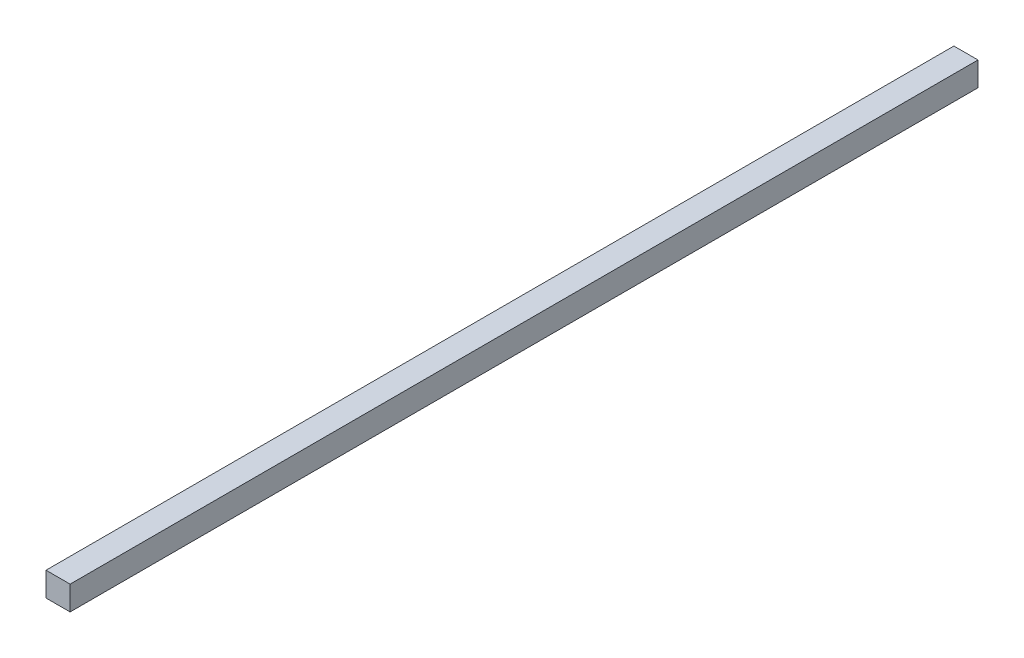
SolidWorks part; units mm, degrees
ref_plane "Front Plane" through (0, 0, 0) normal (0, 0, 1) x (1, 0, 0)
ref_plane "Top Plane" through (0, 0, 0) normal (0, 1, 0) x (1, 0, 0)
ref_plane "Right Plane" through (0, 0, 0) normal (1, 0, 0) x (0, 0, -1)
sketch "Sketch1" plane through (0, 0, 0) normal (1, 0, 0) x (0, 0, -1)
  line L1 (0, 0) -> (452, 0)
  line L2 (0, 0) -> (0, 12)
  line L3 (0, 12) -> (452, 12)
  line L4 (452, 0) -> (452, 12)
  dimension "D1" = 452
  dimension "D2" = 12
extrude "Boss-Extrude1" add sketch "Sketch1" along normal blind 12
